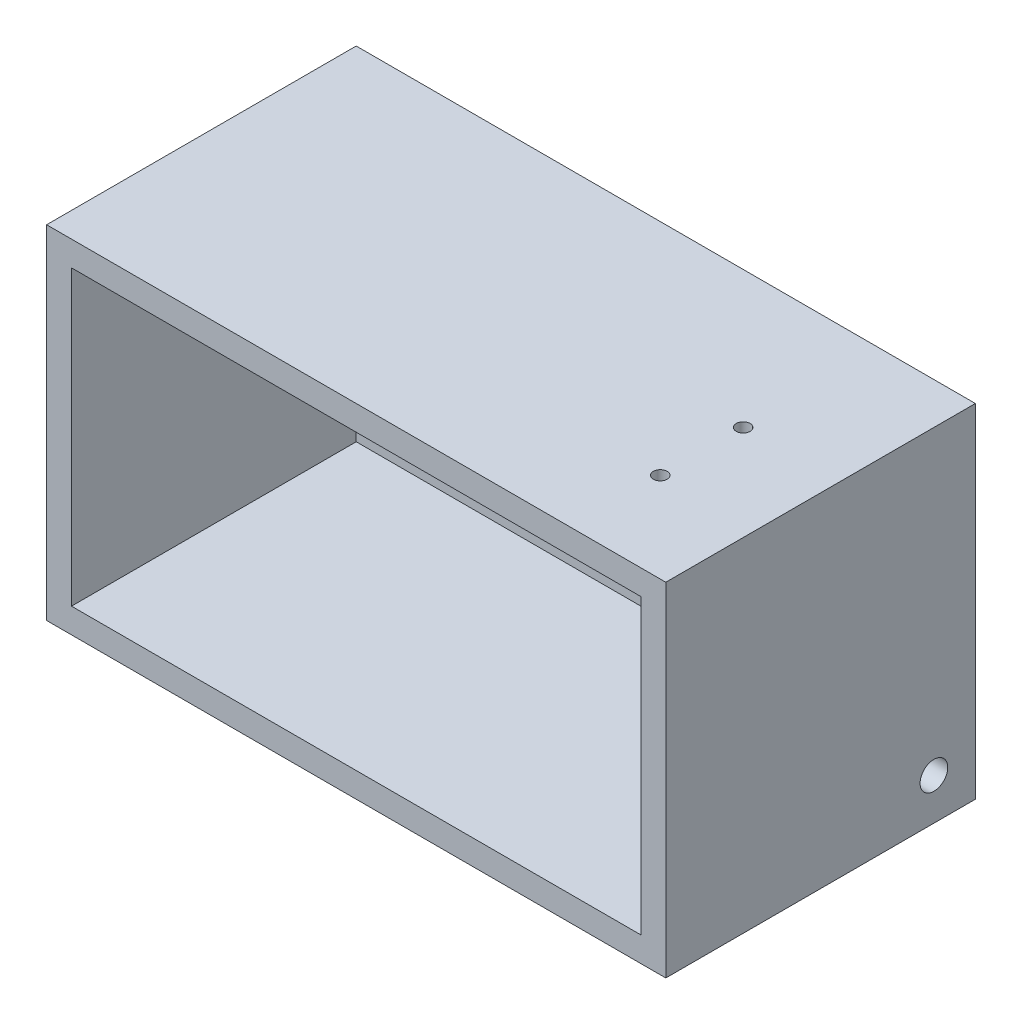
SolidWorks part; units mm, degrees
ref_plane "Front Plane" through (0, 0, 0) normal (0, 0, 1) x (1, 0, 0)
ref_plane "Top Plane" through (0, 0, 0) normal (0, 1, 0) x (1, 0, 0)
ref_plane "Right Plane" through (0, 0, 0) normal (1, 0, 0) x (0, 0, -1)
sketch "Sketch1" plane through (0, 0, 0) normal (0, 0, 1) x (1, 0, 0)
  line L1 (0, 0) -> (448, 0)
  line L2 (0, 0) -> (0, 248)
  line L3 (0, 248) -> (448, 248)
  line L4 (448, 0) -> (448, 248)
  dimension "D1" = 448
  dimension "D2" = 248
extrude "tao_khoi" add sketch "Sketch1" along normal mid plane 224
sketch "Sketch2" plane through (0, 0, 112) normal (0, 0, 1) x (1, 0, 0)
  line L0 (448, 248) -> (0, 248) construction
  line L1 (18, 230) -> (430, 230)
  line L2 (18, 230) -> (18, 18)
  line L3 (18, 18) -> (430, 18)
  line L4 (430, 230) -> (430, 18)
  line L5 (0, 248) -> (0, 0) construction
  dimension "D1" = 412
  dimension "D2" = 212
  dimension "D3" = 18
  dimension "D4" = 18
extrude "tao_vung_dat_vo_trong" cut sketch "Sketch2" against normal blind 206
sketch "Sketch3" plane through (448, 0, 0) normal (1, 0, 0) x (0, 0, -1)
  line L0 (112, 0) -> (112, 248) construction
  line L1 (-112, 0) -> (112, 0) construction
  circle A0 centre (82, 30) radius 10
  dimension "D1" = 20
  dimension "D3" = 30
  dimension "D2" = 30
extrude "tao_lo_di_day_ra_ngoai" cut sketch "Sketch3" against normal up to next
sketch "Sketch5" plane through (0, 248, 0) normal (0, 1, 0) x (1, 0, 0)
  line L0 (448, 112) -> (0, 112) construction
  line L1 (448, -112) -> (448, 112) construction
  circle A0 centre (379, 13) radius 5
  circle A1 centre (379, -47) radius 5
  dimension "D1" = 10
  dimension "D3" = 69
  dimension "D5" = 60
  dimension "D2" = 99
  dimension "D4" = 2
extrude "tao_lo_lay_khi" cut sketch "Sketch5" against normal blind 18
